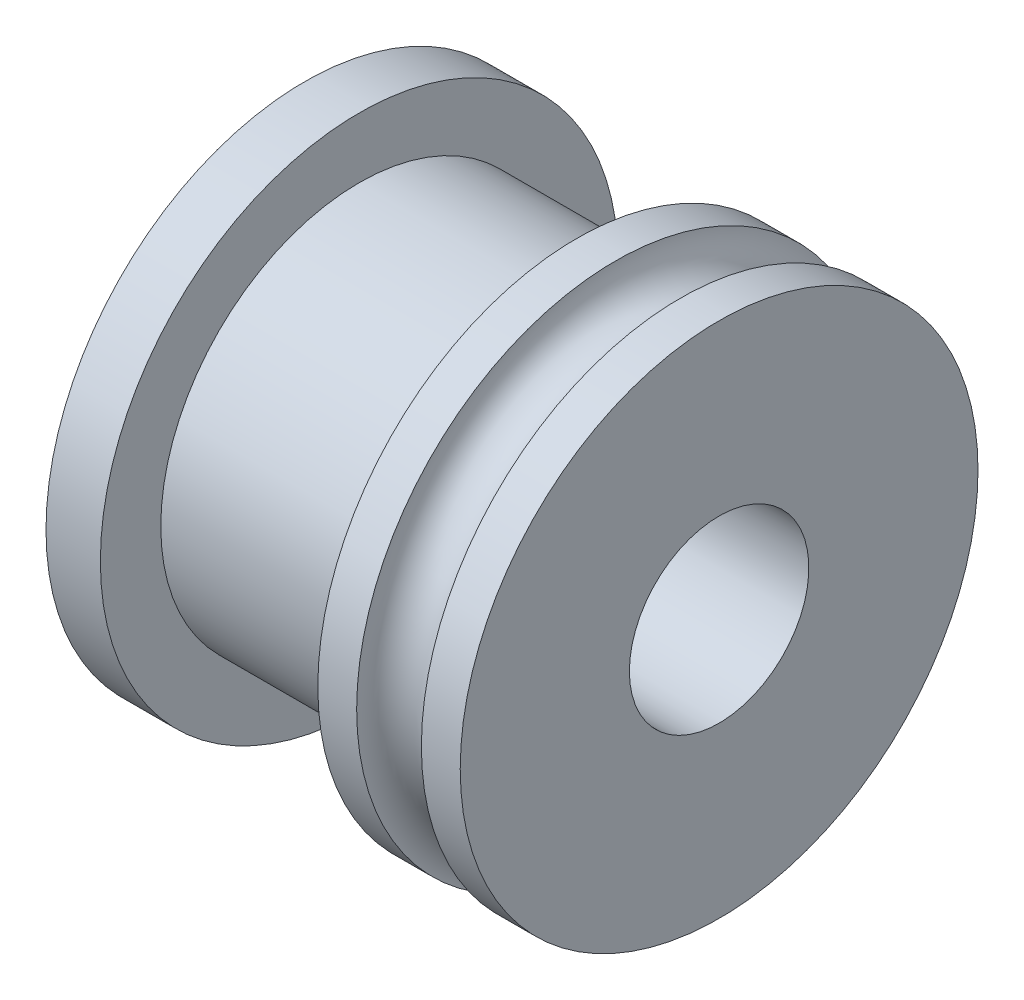
SolidWorks part; units mm, degrees
material "ABS PC"
ref_plane "Front Plane" through (0, 0, 0) normal (0, 0, 1) x (1, 0, 0)
ref_plane "Top Plane" through (0, 0, 0) normal (0, 1, 0) x (1, 0, 0)
ref_plane "Right Plane" through (0, 0, 0) normal (1, 0, 0) x (0, 0, -1)
sketch "Sketch1" plane through (0, 0, 0) normal (0, 0, 1) x (1, 0, 0)
  line L0 (0, 3.302) -> (15.24, 3.302)
  line L1 (15.24, 3.302) -> (15.24, 9.525)
  line L2 (15.24, 9.525) -> (13.8106, 9.525)
  line L3 (10, 9.525) -> (10, 7.302)
  line L4 (10, 7.302) -> (2, 7.302)
  line L5 (2, 7.302) -> (2, 9.525)
  line L6 (2, 9.525) -> (0, 9.525)
  line L7 (0, 9.525) -> (0, 3.302)
  line L8 (0, 0) -> (11.1127, 0) construction
  line L9 (11.4294, 9.525) -> (10, 9.525)
  arc A0 (11.4294, 9.525) -> (13.8106, 9.525) centre (12.62, 9.525) ccw
  point P9 (12.6843, 9.525)
  point P15 (0, 0)
  dimension "D7" = 2.3813
  dimension "D1" = 8
  dimension "D2" = 15.24
  dimension "D3" = 3.302
  dimension "D4" = 4
  dimension "D5" = 9.525
  dimension "D6" = 2
revolve "Revolve1" add sketch "Sketch1" angle 360 about L8
